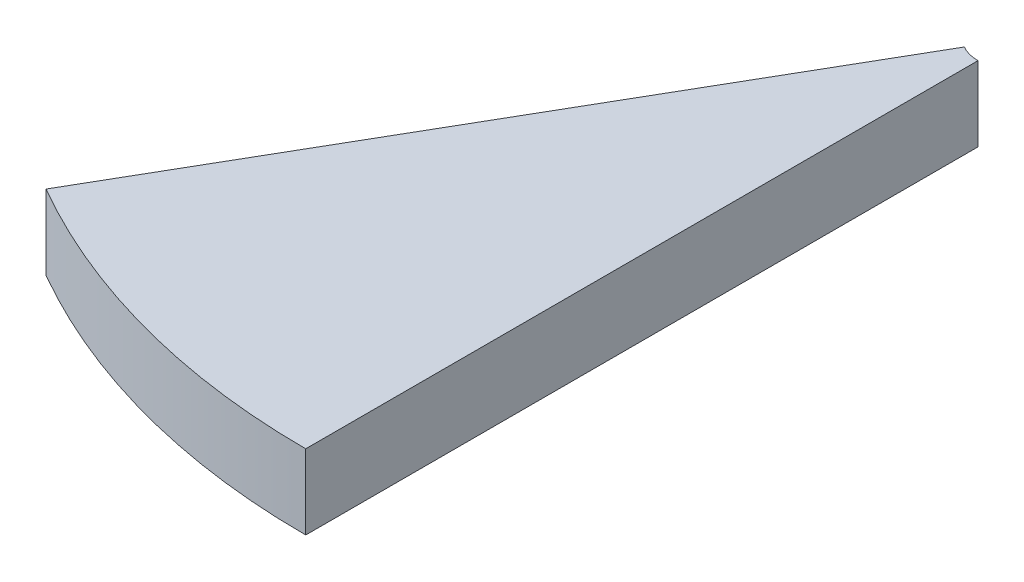
SolidWorks part; units mm, degrees
ref_plane "Front Plane" through (0, 0, 0) normal (0, 0, 1) x (1, 0, 0)
ref_plane "Top Plane" through (0, 0, 0) normal (0, 1, 0) x (1, 0, 0)
ref_plane "Right Plane" through (0, 0, 0) normal (1, 0, 0) x (0, 0, -1)
sketch "Sketch1" plane through (0, 0, 0) normal (0, 1, 0) x (1, 0, 0)
  line L0 (0, -647.3179) -> (0, 25.1904) construction
  line L1 (0, 0) -> (-190, -329.0897)
  line L2 (-25.8833, 0) -> (23.6007, 0) construction
  line L3 (0, 0) -> (10, -17.3205)
  line L4 (0, -380) -> (0, 0)
  circle A0 centre (0, 0) radius 20
  arc A1 (-190, -329.0897) -> (0, -380) centre (0, 0) ccw
  dimension "D1" = 40
  dimension "D2" = 380
  dimension "D4" = 30
  dimension "D5" = 30
extrude "Boss-Extrude1" add sketch "Sketch1" along normal blind 40 contours L1 A1 L3 A0
